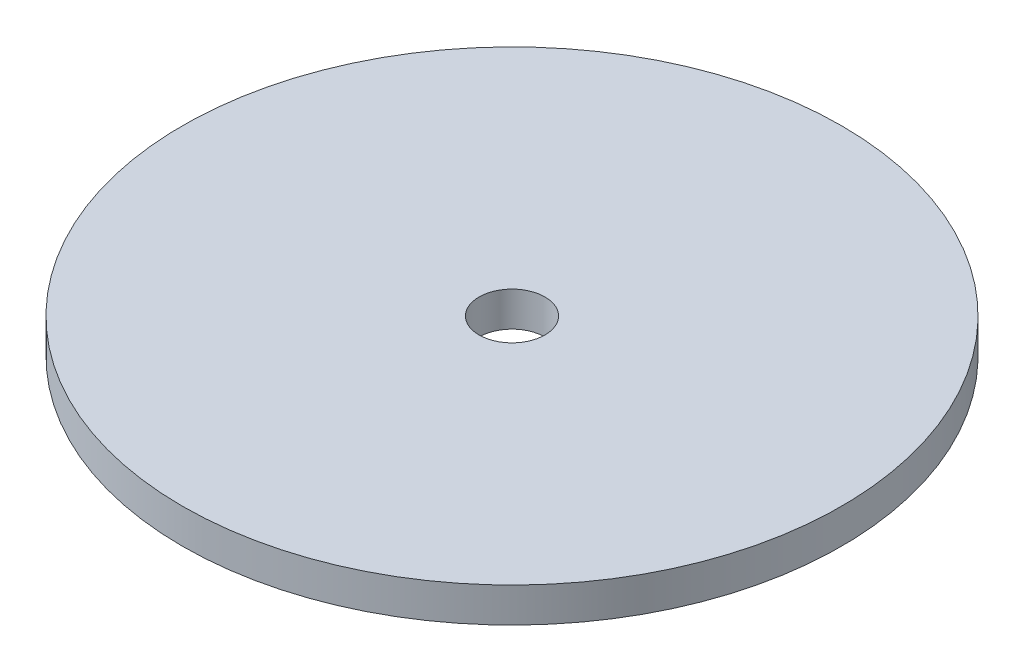
SolidWorks part; units mm, degrees
ref_plane "Front Plane" through (0, 0, 0) normal (0, 0, 1) x (1, 0, 0)
ref_plane "Top Plane" through (0, 0, 0) normal (0, 1, 0) x (1, 0, 0)
ref_plane "Right Plane" through (0, 0, 0) normal (1, 0, 0) x (0, 0, -1)
sketch "Sketch1" plane through (0, 0, 0) normal (0, 1, 0) x (1, 0, 0)
  circle A0 centre (0, 0) radius 48.26
  circle A1 centre (0, 0) radius 4.826
  dimension "D1" = 96.52
  dimension "D2" = 9.652
extrude "Boss-Extrude1" add sketch "Sketch1" along normal blind 5.08
